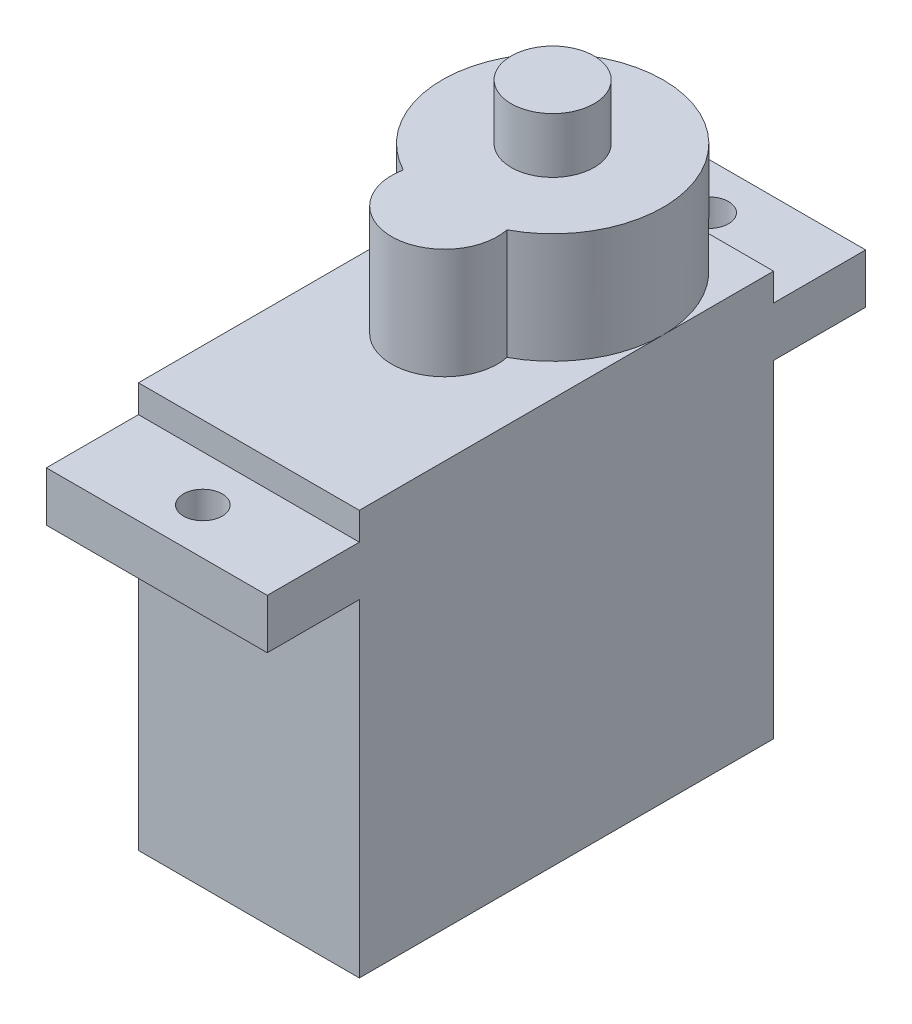
SolidWorks part; units mm, degrees
ref_plane "Front Plane" through (0, 0, 0) normal (0, 0, 1) x (1, 0, 0)
ref_plane "Top Plane" through (0, 0, 0) normal (0, 1, 0) x (1, 0, 0)
ref_plane "Right Plane" through (0, 0, 0) normal (1, 0, 0) x (0, 0, -1)
sketch "Sketch1" plane through (0, 0, 0) normal (1, 0, 0) x (0, 0, -1)
  line L1 (-11.25, -11) -> (11.25, -11)
  line L2 (-11.25, -11) -> (-11.25, 11)
  line L3 (-11.25, 11) -> (11.25, 11)
  line L4 (11.25, -11) -> (11.25, 11)
  line L5 (-11.25, -11) -> (11.25, 11) construction
  line L6 (-11.25, 11) -> (11.25, -11) construction
  line L7 (-11.25, 9.5) -> (-16.25, 9.5)
  line L8 (-11.25, 9.5) -> (-11.25, 6.8)
  line L9 (-11.25, 6.8) -> (-16.25, 6.8)
  line L10 (-16.25, 9.5) -> (-16.25, 6.8)
  line L11 (11.25, 9.5) -> (16.25, 9.5)
  line L12 (11.25, 9.5) -> (11.25, 6.8)
  line L13 (11.25, 6.8) -> (16.25, 6.8)
  line L14 (16.25, 9.5) -> (16.25, 6.8)
  line L15 (11.25, 11) -> (-3.5, 11)
  line L16 (11.25, 11) -> (11.25, 17)
  line L17 (11.25, 17) -> (-3.5, 17)
  line L18 (-3.5, 11) -> (-3.5, 17)
  point P0 (0, 0)
  dimension "D1" = 22
  dimension "D2" = 22.5
  dimension "D3" = 1.5
  dimension "D4" = 1.5
  dimension "D5" = 2.7
  dimension "D6" = 2.7
  dimension "D7" = 5
  dimension "D8" = 5
  dimension "D9" = 6
  dimension "D10" = 14.75
extrude "Boss-Extrude1" add sketch "Sketch1" along normal blind 12 contours L4 L1 L2 L3 | L16 L17 L18 L15 | L7 L10 L9 L8 | L11 L14 L13 L12
sketch "Sketch2" plane through (0, 17, 0) normal (0, 1, 0) x (1, 0, 0)
  line L0 (6, 11.25) -> (6, -3.5)
  line L1 (12, 11.25) -> (0, 11.25) construction
  line L2 (12, -3.5) -> (0, -3.5) construction
  line L3 (6, 11.25) -> (6, 5.25)
  circle A0 centre (6, 5.25) radius 6
  circle A1 centre (6, -0.625) radius 2.875
  line M3 (0, 11.25) -> (0, -3.5)
  line M4 (0, -3.5) -> (12, -3.5)
  line M5 (12, -3.5) -> (12, 11.25)
  line M6 (12, 11.25) -> (0, 11.25)
extrude "Cut-Extrude1" cut sketch "Sketch2" against normal blind 6 contours A0 M6 M3 | A0 M5 M6 | A1 A0 M4 M5 | A1 A0 M3 M4
sketch "Sketch3" plane through (0, 9.5, 0) normal (0, 1, 0) x (1, 0, 0)
  line L0 (0, -13.75) -> (12, -13.75)
  line L1 (0, -11.25) -> (0, -16.25) construction
  line L2 (12, -11.25) -> (12, -16.25) construction
  line L3 (12, -16.25) -> (0, -16.25) construction
  line L4 (6, -16.25) -> (6, -11.25)
  line L5 (12, -11.25) -> (0, -11.25) construction
  line L6 (0, 13.75) -> (12, 13.75)
  line L7 (0, 11.25) -> (0, 16.25) construction
  line L8 (12, 11.25) -> (12, 16.25) construction
  line L9 (6, 16.25) -> (6, 11.25)
  line L10 (12, 16.25) -> (0, 16.25) construction
  line L11 (12, 11.25) -> (0, 11.25) construction
  circle A0 centre (6, -13.75) radius 1.05
  circle A1 centre (6, 13.75) radius 1.05
extrude "Cut-Extrude2" cut sketch "Sketch3" against normal blind 2.7 contours A1 | A0
sketch "Sketch4" plane through (0, 17, 0) normal (0, 1, 0) x (1, 0, 0)
  circle A0 centre (6, 5.25) radius 2.25
extrude "Boss-Extrude3" add sketch "Sketch4" along normal blind 3 contours A0
